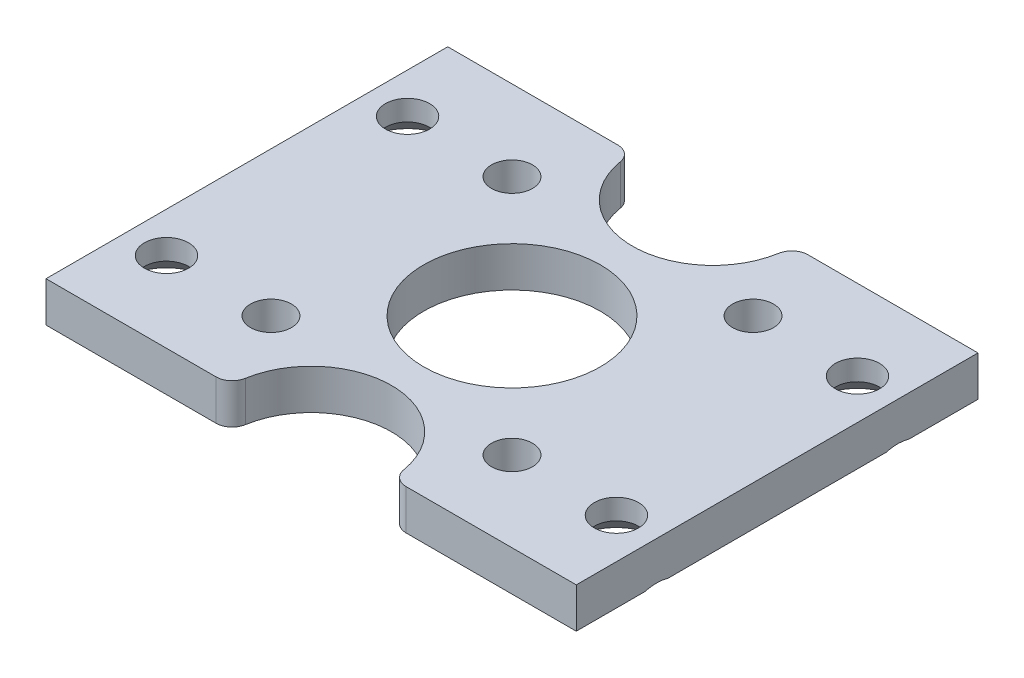
SolidWorks part; units mm, degrees
ref_plane "前视基准面" through (0, 0, 0) normal (0, 0, 1) x (1, 0, 0)
ref_plane "上视基准面" through (0, 0, 0) normal (0, 1, 0) x (1, 0, 0)
ref_plane "右视基准面" through (0, 0, 0) normal (1, 0, 0) x (0, 0, -1)
ref_plane "基准面4" through (0, 0, 0) normal (0, -1, 0) x (1, 0, 0)
sketch "草图1" plane through (0, 0, 0) normal (0, -1, 0) x (1, 0, 0)
  line L0 (66, -50) -> (66, 0)
  line L1 (66, 0) -> (0, 0)
  line L2 (0, 0) -> (0, -50)
  line L3 (0, -50) -> (66, -50)
extrude "凸台-拉伸1" add sketch "草图1" against normal blind 5
hole_wizard "Ø20.0 (20) 直径孔1" positions "草图3" profile "草图2" hole size "Ø20.0" standard "ANSI Metric"
sketch "草图3" plane through (0, 5, 0) normal (0, 1, 0) x (1, 0, 0)
  point P0 (33, 0)
  point P1 (33, 50)
sketch "草图2" plane through (33, 5, 0) normal (1, 0, 0) x (0, 0, 1)
  line L0 (0, 0) -> (0, 5)
  line L1 (0, 5) -> (10, 5)
  line L2 (10, 5) -> (10, 0)
  line L5 (10, 0) -> (0, 0)
  line L11 (0, -6.35) -> (0, 107.95) construction
  dimension "通孔孔直径" = 20
  dimension "通孔孔深度" = 5
hole_wizard "Ø22.0 (22) 直径孔1" positions "草图5" profile "草图4" hole size "Ø22.0" standard "ANSI Metric"
sketch "草图5" plane through (0, 0, 0) normal (0, -1, 0) x (-1, 0, 0)
  point P0 (-33, 25)
sketch "草图4" plane through (33, 0, -25) normal (1, 0, 0) x (0, 0, -1)
  line L0 (0, 0) -> (0, 5)
  line L1 (0, 5) -> (11, 5)
  line L2 (11, 5) -> (11, 0)
  line L5 (11, 0) -> (0, 0)
  line L11 (0, -6.35) -> (0, 107.95) construction
  dimension "通孔孔直径" = 22
  dimension "通孔孔深度" = 5
hole_wizard "Ø5.1 (5.1) 直径孔1" positions "草图7" profile "草图6" hole size "Ø5.1" standard "ANSI Metric"
sketch "草图7" plane through (0, 0, 0) normal (0, -1, 0) x (-1, 0, 0)
  point P0 (-18, 10)
  point P1 (-48, 40)
  point P2 (-48, 10)
  point P3 (-18, 40)
sketch "草图6" plane through (18, 0, -10) normal (1, 0, 0) x (0, 0, -1)
  line L0 (0, 0) -> (0, 5)
  line L1 (0, 5) -> (2.55, 5)
  line L2 (2.55, 5) -> (2.55, 0)
  line L5 (2.55, 0) -> (0, 0)
  line L11 (0, -6.35) -> (0, 107.95) construction
  dimension "通孔孔直径" = 5.1
  dimension "通孔孔深度" = 5
hole_wizard "M5 平头机械螺钉的锥形沉头孔1" positions "草图9" profile "草图8" countersink size "M5" standard "ANSI Metric"
sketch "草图9" plane through (0, 0, 0) normal (0, -1, 0) x (-1, 0, 0)
  point P0 (-5, 40)
  point P1 (-5, 10)
  point P2 (-61, 10)
  point P3 (-61, 40)
sketch "草图8" plane through (5, 0, -40) normal (1, 0, 0) x (0, 0, -1)
  line L0 (0, 0) -> (0, 5)
  line L1 (0, 5) -> (2.75, 5)
  line L2 (2.75, 5) -> (2.75, 2.45)
  line L3 (2.75, 2.45) -> (5.2, 0)
  line L5 (5.2, 0) -> (0, 0)
  line L6 (-2.75, 2.45) -> (-5.2, 0) construction
  line L11 (0, -6.35) -> (0, 107.95) construction
  dimension "通孔孔直径" = 5.5
  dimension "通孔孔深度" = 5
  dimension "近端锥形沉头孔直径" = 10.4
  dimension "近端锥形沉头孔角度" = 90
fillet "圆角1" radius 2 4 edges at (23, 2.5, -50) (43, 2.5, -50) (43, 2.5, 0) (23, 2.5, 0)
